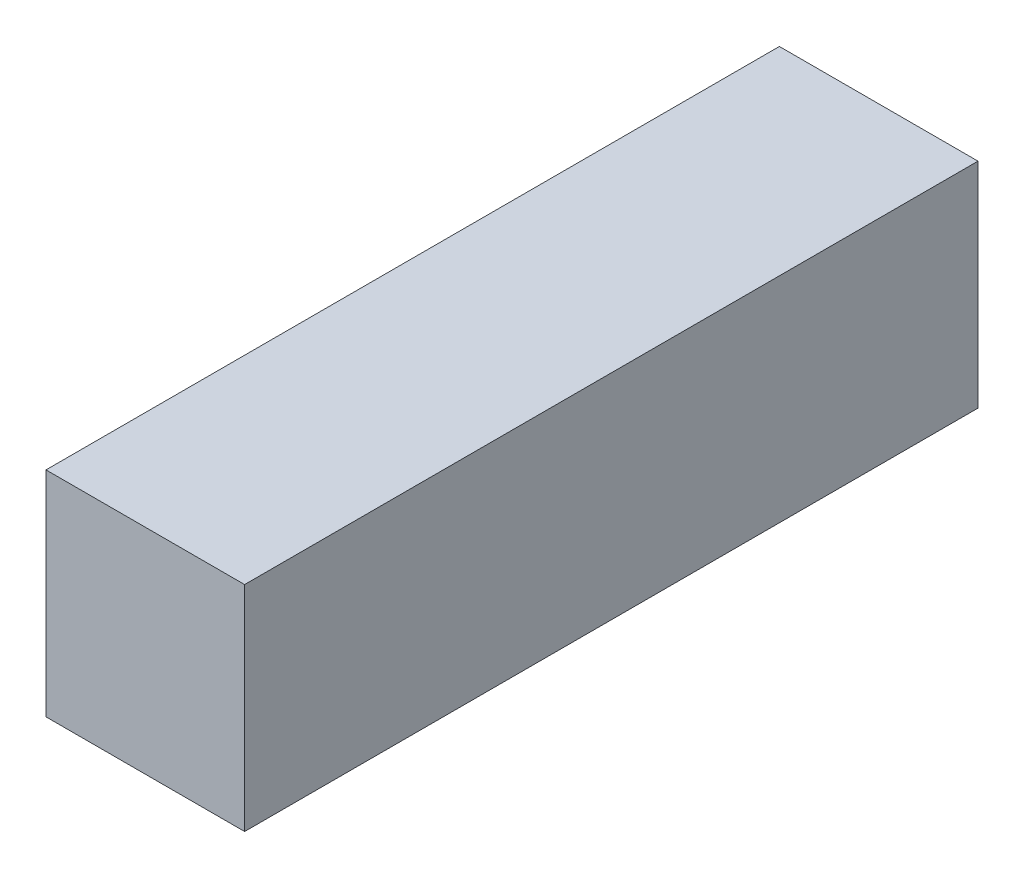
SolidWorks part; units mm, degrees
ref_plane "Front Plane" through (0, 0, 0) normal (0, 0, 1) x (1, 0, 0)
ref_plane "Top Plane" through (0, 0, 0) normal (0, 1, 0) x (1, 0, 0)
ref_plane "Right Plane" through (0, 0, 0) normal (1, 0, 0) x (0, 0, -1)
sketch "Sketch1" plane through (0, 0, 0) normal (0, 0, 1) x (1, 0, 0)
  line L1 (0, 0) -> (41.275, 0)
  line L2 (0, 0) -> (0, 44.45)
  line L3 (0, 44.45) -> (41.275, 44.45)
  line L4 (41.275, 0) -> (41.275, 44.45)
  dimension "D1" = 44.45
  dimension "D2" = 41.275
extrude "Boss-Extrude1" add sketch "Sketch1" along normal blind 152.4
